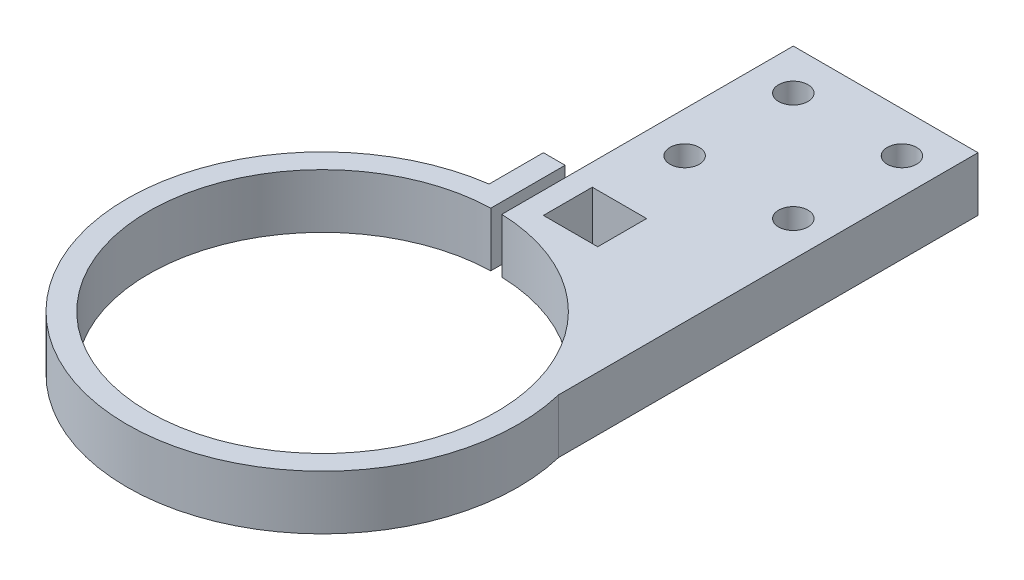
SolidWorks part; units mm, degrees
ref_plane "Front Plane" through (0, 0, 0) normal (0, 0, 1) x (1, 0, 0)
ref_plane "Top Plane" through (0, 0, 0) normal (0, 1, 0) x (1, 0, 0)
ref_plane "Right Plane" through (0, 0, 0) normal (1, 0, 0) x (0, 0, -1)
sketch "Sketch1" plane through (0, 0, 0) normal (0, 1, 0) x (1, 0, 0)
  circle A0 centre (0, 0) radius 40.64
  circle A1 centre (0, 0) radius 45.72
  dimension "D1" = 81.28
  dimension "D2" = 91.44
extrude "Boss-Extrude1" add sketch "Sketch1" along normal blind 12.7
sketch "Sketch2" plane through (0, 0, 0) normal (0, 1, 0) x (1, 0, 0)
  line L1 (6.35, 57.9769) -> (-6.35, 57.9769)
  line L2 (6.35, 57.9769) -> (6.35, 45.2769)
  line L3 (6.35, 45.2769) -> (-6.35, 45.2769)
  line L4 (-6.35, 57.9769) -> (-6.35, 45.2769)
  line L5 (6.35, 57.9769) -> (-6.35, 45.2769) construction
  line L6 (6.35, 45.2769) -> (-6.35, 57.9769) construction
  circle A0 centre (0, 0) radius 45.72 construction
  point P0 (0, 51.6269)
  point P7 (0, 0)
  dimension "D1" = 12.7
  dimension "D2" = 12.7
extrude "Boss-Extrude2" add sketch "Sketch2" along normal blind 12.7
sketch "Sketch4" plane through (0, 0, 0) normal (0, 1, 0) x (1, 0, 0)
  line L1 (-1.27, 39.7899) -> (1.27, 39.7899)
  line L2 (-1.27, 39.7899) -> (-1.27, 60.42)
  line L3 (-1.27, 60.42) -> (1.27, 60.42)
  line L4 (1.27, 39.7899) -> (1.27, 60.42)
  line L5 (-1.27, 39.7899) -> (1.27, 60.42) construction
  line L6 (-1.27, 60.42) -> (1.27, 39.7899) construction
  point P0 (0, 50.105)
  point P7 (0, 0)
  dimension "D1" = 2.54
extrude "Cut-Extrude2" cut sketch "Sketch4" along normal through all
sketch "Sketch5" plane through (6.35, 0, 0) normal (1, 0, 0) x (0, 0, -1)
  line L1 (57.9769, 12.7) -> (0, 12.7)
  line L2 (57.9769, 12.7) -> (57.9769, 0)
  line L3 (57.9769, 0) -> (0, 0)
  line L4 (0, 12.7) -> (0, 0)
extrude "Boss-Extrude3" add sketch "Sketch5" against normal up to next from offset 38.1
sketch "Sketch6" plane through (0, 12.7, 0) normal (0, 1, 0) x (1, 0, 0)
  line L0 (1.27, 40.6202) -> (1.27, 57.9769) construction
  line L1 (44.45, 57.9769) -> (1.27, 57.9769)
  line L2 (44.45, 57.9769) -> (44.45, 108.7769)
  line L3 (44.45, 108.7769) -> (1.27, 108.7769)
  line L4 (1.27, 57.9769) -> (1.27, 108.7769)
  dimension "D1" = 50.8
extrude "Boss-Extrude4" add sketch "Sketch6" against normal blind 12.7
sketch "Sketch7" plane through (0, 0, 0) normal (0, 1, 0) x (1, 0, 0)
  line L0 (44.45, 108.7769) -> (1.27, 108.7769) construction
  line L2 (1.27, 40.6202) -> (1.27, 108.7769) construction
  line L4 (6.35, 56.7069) -> (19.05, 56.7069)
  line L5 (6.35, 56.7069) -> (6.35, 45.2769)
  line L6 (6.35, 45.2769) -> (19.05, 45.2769)
  line L7 (19.05, 56.7069) -> (19.05, 45.2769)
  circle A0 centre (10.795, 99.2519) radius 3.429
  circle A1 centre (36.195, 99.2519) radius 3.429
  circle A2 centre (36.195, 73.8519) radius 3.429
  circle A3 centre (10.795, 73.8519) radius 3.429
  point P16 (0, 0)
  point P18 (0, 0)
  point P20 (0, 0)
  dimension "D1" = 6.858
  dimension "D2" = 9.525
  dimension "D3" = 9.525
  dimension "D6" = 11.43
  dimension "D7" = 5.08
  dimension "D8" = 12.7
  dimension "D4" = 2
  dimension "D5" = 2
extrude "Cut-Extrude3" cut sketch "Sketch7" along normal through all
